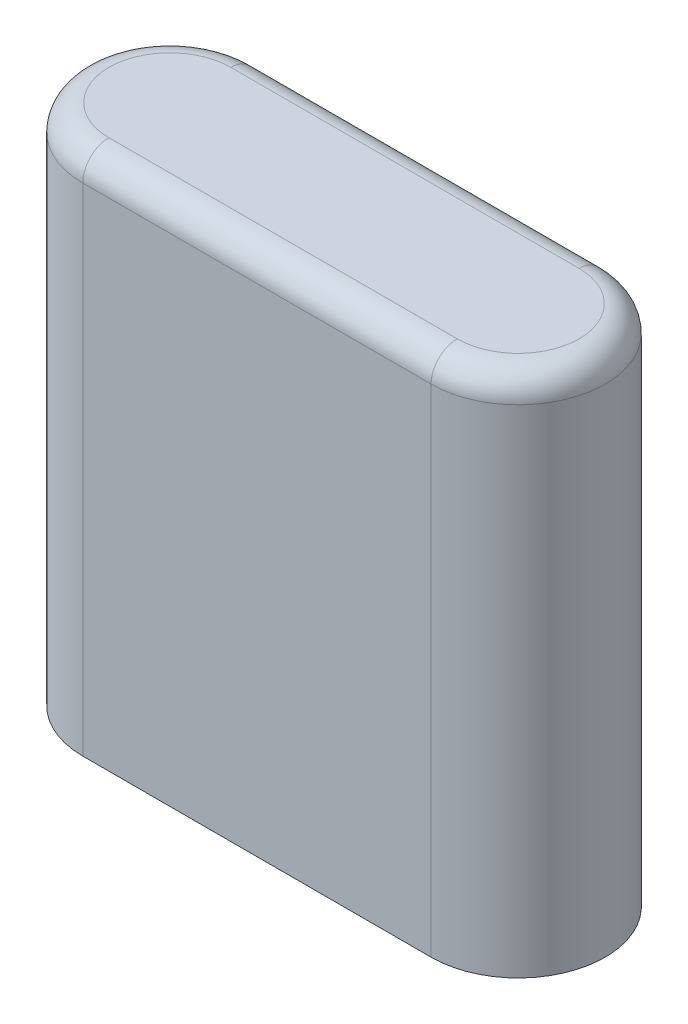
SolidWorks part; units mm, degrees
ref_plane "前视基准面" through (0, 0, 0) normal (0, 0, 1) x (1, 0, 0)
ref_plane "上视基准面" through (0, 0, 0) normal (0, 1, 0) x (1, 0, 0)
ref_plane "右视基准面" through (0, 0, 0) normal (1, 0, 0) x (0, 0, -1)
sketch "草图1" plane through (0, 0, 0) normal (0, 1, 0) x (1, 0, 0)
  line L0 (-20, 0) -> (20, 0) construction
  line L1 (-20, 10) -> (20, 10)
  line L2 (-20, -10) -> (20, -10)
  arc A0 (-20, 10) -> (-20, -10) centre (-20, 0) ccw
  arc A1 (20, -10) -> (20, 10) centre (20, 0) ccw
  point P3 (0, 0)
  dimension "D1" = 10
  dimension "D2" = 40
extrude "凸台-拉伸1" add sketch "草图1" along normal mid plane 60
fillet "圆角1" radius 3 4 edges at (0, 30, -10) (30, 30, 0) (0, 30, 10) (-30, 30, 0)
sketch "草图2" plane through (0, -30, 0) normal (0, -1, 0) x (1, 0, 0)
  line L0 (0, 0) -> (0, 10) construction
  line L1 (-20, 10) -> (20, 10) construction
  circle A0 centre (-20, 0) radius 3
  circle A1 centre (20, 0) radius 4.5
  circle A2 centre (20, 0) radius 3
  dimension "D1" = 6
  dimension "D2" = 6
  dimension "D3" = 9
  dimension "D4" = 40
extrude "凸台-拉伸2" add sketch "草图2" along normal blind 3
